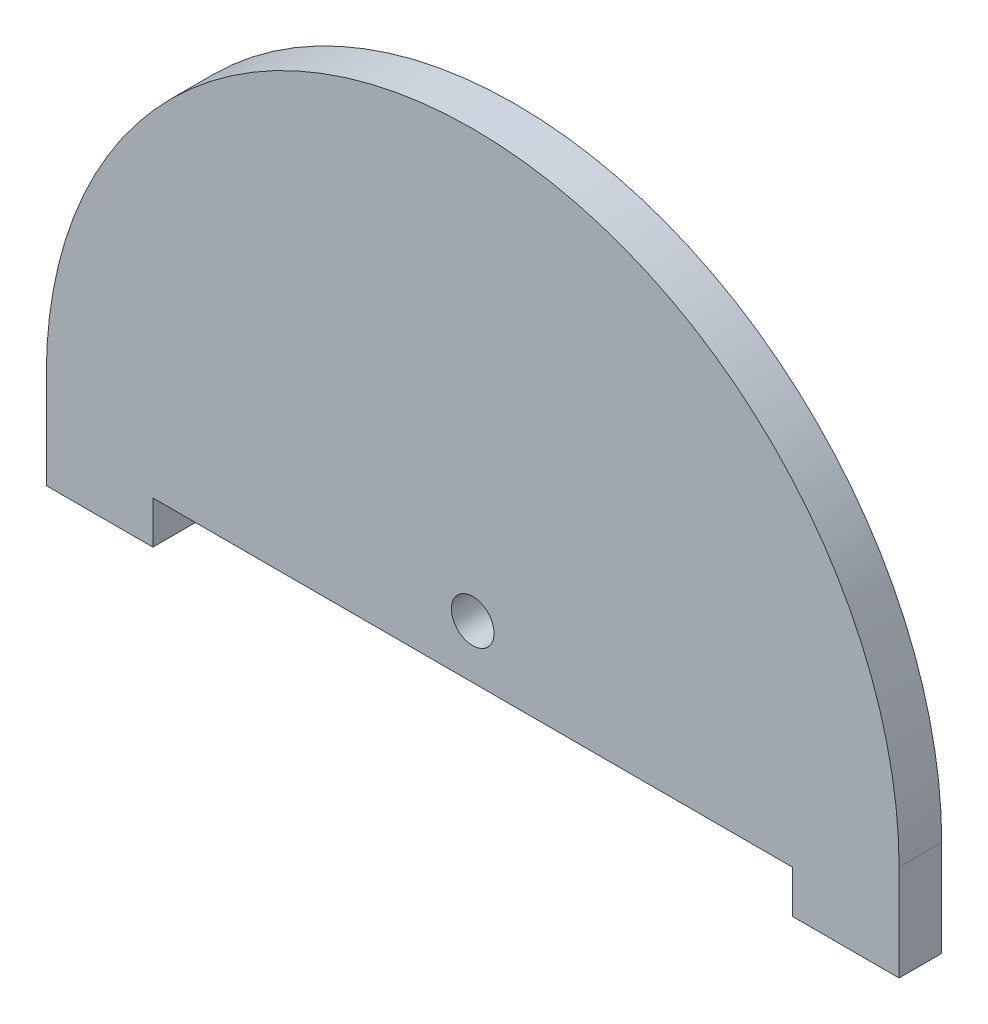
SolidWorks part; units mm, degrees
ref_plane "Front Plane" through (0, 0, 0) normal (0, 0, 1) x (1, 0, 0)
ref_plane "Top Plane" through (0, 0, 0) normal (0, 1, 0) x (1, 0, 0)
ref_plane "Right Plane" through (0, 0, 0) normal (1, 0, 0) x (0, 0, -1)
sketch "Sketch1" plane through (0, 0, 0) normal (0, 0, 1) x (1, 0, 0)
  line L0 (-80, 0) -> (80, 0)
  line L1 (0, 0) -> (0, 80) construction
  arc A0 (-80, 0) -> (80, 0) centre (0, 0) cw
  dimension "D1" = 160
  dimension "D2" = 80
extrude "Boss-Extrude1" add sketch "Sketch1" along normal blind 8
sketch "Sketch5" plane through (0, 0, 0) normal (0, -1, 0) x (1, 0, 0)
  line L1 (-80, 8) -> (80, 8)
  line L2 (-80, 8) -> (-80, 0)
  line L3 (-80, 0) -> (80, 0)
  line L4 (80, 8) -> (80, 0)
extrude "Boss-Extrude4" add sketch "Sketch5" along normal blind 10
sketch "Sketch6" plane through (0, -10, 0) normal (0, -1, 0) x (1, 0, 0)
  line L0 (-80, 0) -> (80, 0) construction
  line L1 (-80, 8) -> (-60, 8)
  line L2 (-80, 8) -> (-80, 0)
  line L3 (-80, 0) -> (-60, 0)
  line L4 (-60, 8) -> (-60, 0)
  dimension "D1" = 20
extrude "Boss-Extrude5" add sketch "Sketch6" along normal blind 8
mirror "Mirror2" about plane through (0, 0, 0) normal (1, 0, 0) of "Boss-Extrude5"
sketch "Sketch7" plane through (0, 0, 8) normal (0, 0, 1) x (1, 0, 0)
  line L0 (0, 0) -> (0, -10) construction
  line L1 (60, -10) -> (-60, -10) construction
  circle A0 centre (0, 0) radius 4
  dimension "D1" = 8
extrude "Cut-Extrude2" cut sketch "Sketch7" against normal blind 8
